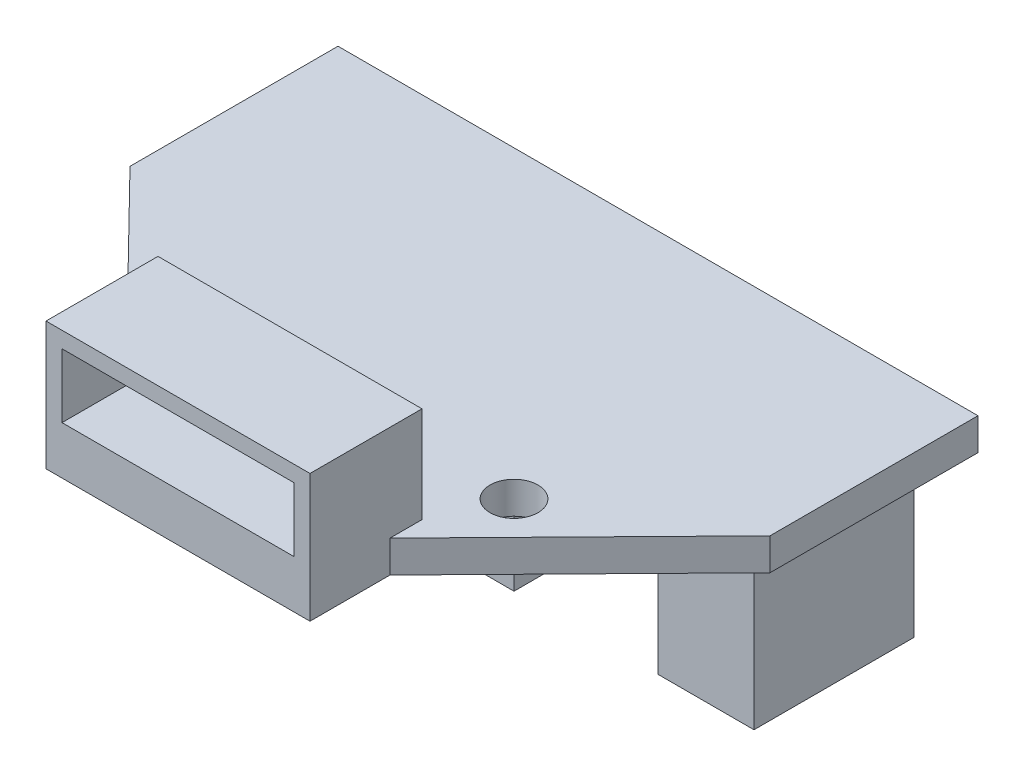
SolidWorks part; units mm, degrees
ref_plane "前视基准面" through (0, 0, 0) normal (0, 0, 1) x (1, 0, 0)
ref_plane "上视基准面" through (0, 0, 0) normal (0, 1, 0) x (1, 0, 0)
ref_plane "右视基准面" through (0, 0, 0) normal (1, 0, 0) x (0, 0, -1)
sketch "草图1" plane through (0, 0, 0) normal (0, 1, 0) x (1, 0, 0)
  line L0 (-20, 15) -> (20, 15)
  line L1 (20, 15) -> (20, 2)
  line L3 (8.25, -15) -> (-8.25, -15)
  line L5 (-20, 2) -> (-20, 15)
  line L6 (0, 15) -> (0, -15) construction
  line L7 (-20, 2) -> (-8.25, -10)
  line L8 (-8.25, -10) -> (-8.25, -15)
  line L9 (20, 2) -> (8.25, -10)
  line L10 (8.25, -10) -> (8.25, -15)
  circle A0 centre (-10, -4) radius 1.5
  circle A1 centre (10, -4) radius 1.5
  point P8 (0, 0)
  point P16 (0, 0)
  dimension "D6" = 3
  dimension "D1" = 40
  dimension "D2" = 30
  dimension "D3" = 13
  dimension "D4" = 16.5
  dimension "D5" = 5
  dimension "D7" = 20
  dimension "D8" = 11
extrude "凸台-拉伸1" add sketch "草图1" along normal blind 2
sketch "草图2" plane through (0, 2, 0) normal (0, 1, 0) x (1, 0, 0)
  line L1 (-8.25, -15) -> (8.25, -15)
  line L2 (-8.25, -15) -> (-8.25, -8)
  line L3 (-8.25, -8) -> (8.25, -8)
  line L4 (8.25, -15) -> (8.25, -8)
  point P5 (8.8018, -15)
  point P6 (8.25, -15)
  dimension "D1" = 7
extrude "凸台-拉伸2" add sketch "草图2" along normal blind 6
sketch "草图3" plane through (0, 0, 0) normal (0, -1, 0) x (1, 0, 0)
  line L0 (0, -8) -> (0, -15) construction
  line L1 (-3, -3) -> (3, -3)
  line L2 (-3, -3) -> (-3, -13)
  line L3 (-3, -13) -> (3, -13)
  line L4 (3, -3) -> (3, -13)
  line L5 (-3, -3) -> (3, -13) construction
  line L6 (-3, -13) -> (3, -3) construction
  line L7 (20, -15) -> (-20, -15) construction
  point P0 (0, -8)
  dimension "D1" = 6
  dimension "D2" = 10
  dimension "D3" = 2
extrude "凸台-拉伸3" add sketch "草图3" along normal blind 10
pattern_linear "阵列(线性)1" count 2 spacing 15 along (1, 0, 0) of "凸台-拉伸3"
pattern_linear "阵列(线性)2" count 2 spacing 15 along (-1, 0, 0) of "凸台-拉伸3"
sketch "草图4" plane through (0, 0, 15) normal (0, 0, 1) x (1, 0, 0)
  line L0 (0, 5) -> (0, 0) construction
  line L1 (-7.25, 3) -> (7.25, 3)
  line L2 (-7.25, 3) -> (-7.25, 7)
  line L3 (-7.25, 7) -> (7.25, 7)
  line L4 (7.25, 3) -> (7.25, 7)
  line L5 (-7.25, 3) -> (7.25, 7) construction
  line L6 (-7.25, 7) -> (7.25, 3) construction
  line L7 (-8.25, 0) -> (8.25, 0) construction
  line L8 (8.25, 8) -> (8.25, 0) construction
  line L9 (8.25, 2) -> (20, 2) construction
  line L10 (-8.25, 8) -> (8.25, 8) construction
  point P0 (0, 5)
  dimension "D1" = 1
  dimension "D2" = 1
  dimension "D3" = 1
extrude "切除-拉伸1" cut sketch "草图4" against normal blind 5
